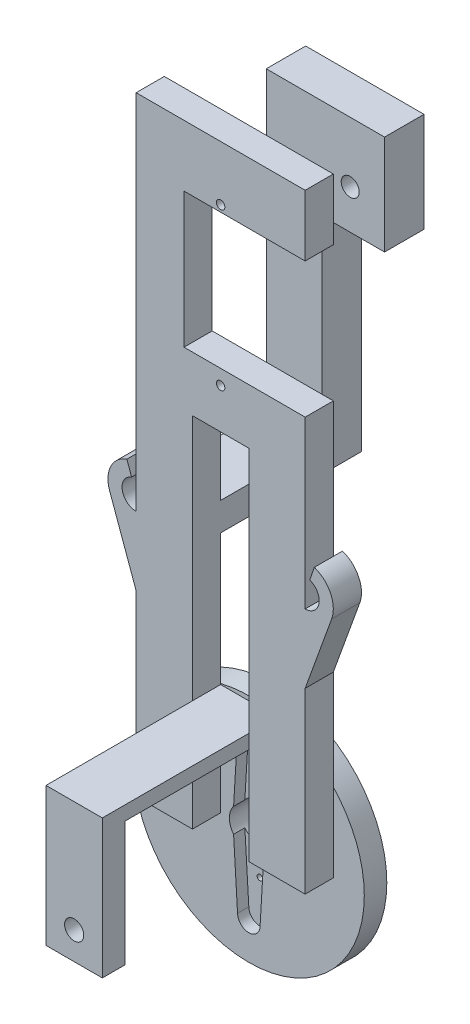
SolidWorks part; units mm, degrees
ref_plane "Front Plane" through (0, 0, 0) normal (0, 0, 1) x (1, 0, 0)
ref_plane "Top Plane" through (0, 0, 0) normal (0, 1, 0) x (1, 0, 0)
ref_plane "Right Plane" through (0, 0, 0) normal (1, 0, 0) x (0, 0, -1)
sketch "Sketch2" plane through (0, 0, 0) normal (0, 0, 1) x (1, 0, 0)
  line L0 (-32, -13.925) -> (-32.7, -2.1477)
  line L1 (-32.7, 2.1477) -> (-32, 13.925)
  line L2 (-28, 13.925) -> (-27.3, 2.1477)
  line L3 (-28, -13.925) -> (-27.3, -2.1477)
  line L4 (-28.2556, -14.0649) -> (-27.3, -2.1477) construction
  arc A1 (-28, 13.925) -> (-32, 13.925) centre (-30, 13.925) ccw
  arc A2 (-32, -13.925) -> (-28, -13.925) centre (-30, -13.925) ccw
  arc A4 (-27.3, -2.1477) -> (-27.3, 2.1477) centre (-30, 0) ccw
  arc A5 (-32.7, 2.1477) -> (-32.7, -2.1477) centre (-30, 0) ccw
  circle A6 centre (-30, 0) radius 20.5
  dimension "D1" = 41
  dimension "D2" = 2
  dimension "D3" = 2
extrude "Boss-Extrude1" add sketch "Sketch2" against normal blind 4
sketch "Sketch3" plane through (0, 0, -4) normal (0, 0, -1) x (-1, 0, 0)
  line L0 (32, 13.925) -> (32.7, 2.1477)
  line L1 (32.7, -2.1477) -> (32, -13.925)
  line L2 (28, -13.925) -> (27.3, -2.1477)
  line L3 (28, 13.925) -> (27.3, 2.1477)
  arc A0 (32.7, 2.1477) -> (27.3, 2.1477) centre (30, 0) ccw
  arc A1 (28, -13.925) -> (32, -13.925) centre (30, -13.925) ccw
  arc A2 (32, 13.925) -> (28, 13.925) centre (30, 13.925) ccw
  arc A3 (27.3, -2.1477) -> (32.7, -2.1477) centre (30, 0) ccw
extrude "Boss-Extrude2" add sketch "Sketch3" against normal blind 2
sketch "Sketch4" plane through (0, 0, 0) normal (0, 0, 1) x (1, 0, 0)
  line L0 (-50.5, 0) -> (-9.5, 0) construction
  line L1 (-30, 20.5) -> (-30, -20.5) construction
  line L3 (-45, 0) -> (-35, 0)
  line L4 (-45, 0) -> (-45, 66.4807)
  line L6 (-35, 0) -> (-35, 63.5566)
  line L8 (-45, 45) -> (-35, 45) construction
  line L9 (-25, 0) -> (-25, 63.5566)
  line L10 (-15, 0) -> (-25, 0)
  line L11 (-15, 0) -> (-15, 66.4807)
  line L13 (-45, 108.2058) -> (-15, 108.2058)
  line L14 (-45, 108.2058) -> (-45, 66.4807)
  line L15 (-35, 63.5566) -> (-25, 63.5566)
  line L16 (-15, 108.2058) -> (-15, 66.4807)
  line L17 (-30, 60.6324) -> (-30, 108.2058) construction
  line L22 (-30, 73.2926) -> (-30, 96.1526) construction
  line L24 (-33.6892, 97.3307) -> (-50033.6892, 97.3307) construction
  line L26 (-35.3887, 73.3307) -> (-50035.3887, 73.3307) construction
  line L28 (-36.5, 74.4318) -> (-36.5, 50074.4318) construction
  line L30 (-23.5, 99.0932) -> (-23.5, -49900.9068) construction
  line L33 (-36.5, 97.3307) -> (-23.5, 97.3307)
  line L34 (-36.5, 97.3307) -> (-36.5, 73.3307)
  line L35 (-36.5, 73.3307) -> (-23.5, 73.3307)
  line L36 (-23.5, 97.3307) -> (-23.5, 73.3307)
  line L37 (-30, 73.3307) -> (-30, 97.3307) construction
  line L38 (-36.5, 85.3307) -> (-23.5, 85.3307) construction
  circle A0 centre (-30, 0) radius 20.5 construction
  circle A4 centre (-30, 70.6807) radius 0.75
  circle A5 centre (-30, 98.4807) radius 0.75
  point P317 (-30, 84.7226)
  point P606 (-30, 85.3307)
  point P879 (-30, 87.3433)
  point P1483 (-40, 45)
  dimension "D4" = 1.5
  dimension "D5" = 24
  dimension "D3" = 1.5
  dimension "D6" = 13
  dimension "D1" = 5
  dimension "D2" = 10
extrude "Boss-Extrude3" add sketch "Sketch4" along normal blind 5
sketch "Sketch5" plane through (0, 0, 0) normal (0, 0, -1) x (-1, 0, 0)
  line L0 (35, 19.8809) -> (35, 63.5566) construction
  line L1 (35, 48.0311) -> (45, 48.0311)
  line L2 (35, 48.0311) -> (35, 43.0311)
  line L3 (35, 43.0311) -> (45, 43.0311)
  line L4 (45, 48.0311) -> (45, 43.0311)
  line L5 (40, 43.0311) -> (40, 48.0311) construction
  line L6 (35, 45.5311) -> (45, 45.5311) construction
  line L7 (45, 108.2058) -> (45, 13.9732) construction
  point P208 (40, 45.5311)
  dimension "D1" = 5
extrude "Boss-Extrude4" add sketch "Sketch5" along normal blind 25
sketch "Sketch6" plane through (0, 48.0311, 0) normal (0, 1, 0) x (1, 0, 0)
  line L0 (-45, 25) -> (-35, 25) construction
  line L1 (-44.9019, 25) -> (-23.9019, 25)
  line L2 (-44.9019, 25) -> (-44.9019, 18)
  line L3 (-44.9019, 18) -> (-23.9019, 18)
  line L4 (-23.9019, 25) -> (-23.9019, 18)
  line L5 (-34.4019, 18) -> (-34.4019, 25) construction
  line L6 (-44.9019, 21.5) -> (-23.9019, 21.5) construction
  point P912 (-34.4019, 21.5)
  dimension "D1" = 21
  dimension "D2" = 7
extrude "Boss-Extrude5" add sketch "Sketch6" along normal blind 52.4
sketch "Sketch7" plane through (0, 0, -25) normal (0, 0, -1) x (-1, 0, 0)
  circle A0 centre (30, 89.7307) radius 1.6
  dimension "D1" = 3.2
extrude "Cut-Extrude1" cut sketch "Sketch7" against normal blind 52.4
sketch "Sketch8" plane through (0, 0, 0) normal (0, 0, 1) x (1, 0, 0)
  line L0 (-30, 15.925) -> (-30, -15.925) construction
  arc A0 (-28, 13.925) -> (-32, 13.925) centre (-30, 13.925) ccw construction
  arc A1 (-32, -13.925) -> (-28, -13.925) centre (-30, -13.925) ccw construction
  circle A2 centre (-29.9753, 10.435) radius 0.5
  circle A3 centre (-30.02, -8.465) radius 0.5
extrude "Cut-Extrude2" cut sketch "Sketch8" against normal blind 10
sketch "Sketch9" plane through (0, 0, 5) normal (0, 0, 1) x (1, 0, 0)
  line L0 (-15, 0) -> (-15, 108.2058) construction
  line L1 (-23.5, 73.3307) -> (-15, 73.3307)
  line L2 (-23.5, 73.3307) -> (-23.5, 97.3307)
  line L3 (-23.5, 97.3307) -> (-15, 97.3307)
  line L4 (-15, 73.3307) -> (-15, 97.3307)
  line L5 (-19.25, 97.3307) -> (-19.25, 73.3307) construction
  line L6 (-23.5, 85.3307) -> (-15, 85.3307) construction
  point P568 (-19.25, 85.3307)
extrude "Cut-Extrude3" cut sketch "Sketch9" against normal blind 10
sketch "Sketch10" plane through (0, 0, 0) normal (0, 0, 1) x (1, 0, 0)
  line L0 (-30, 20.5) -> (-30, -20.5) construction
  line L1 (-25, 63.5566) -> (-25, 0) construction
  line L2 (-35, 19.7172) -> (-25, 19.7172)
  line L3 (-35, 19.7172) -> (-35, 17.2116)
  line L4 (-35, 17.2116) -> (-25, 17.2116)
  line L5 (-25, 19.7172) -> (-25, 17.2116)
  line L6 (-35, 19.7172) -> (-25, 17.2116) construction
  line L7 (-35, 17.2116) -> (-25, 19.7172) construction
  arc A0 (-25, 19.8809) -> (-35, 19.8809) centre (-30, 0) ccw construction
  arc A1 (-45, 13.9732) -> (-15, 13.9732) centre (-30, 0) ccw construction
  point P8 (-30, 18.4644)
extrude "Boss-Extrude6" add sketch "Sketch10" along normal blind 31
sketch "Sketch11" plane through (0, 0, 31) normal (0, 0, 1) x (1, 0, 0)
  line L1 (-35, 19.7172) -> (-25, 19.7172)
  line L2 (-35, 19.7172) -> (-35, -4.8872)
  line L3 (-35, -4.8872) -> (-25, -4.8872)
  line L4 (-25, 19.7172) -> (-25, -4.8872)
  line L5 (-30, -4.8872) -> (-30, 19.7172) construction
  line L6 (-35, 7.415) -> (-25, 7.415) construction
  circle A0 centre (-30, 0) radius 1.7
  point P1711 (-30, 7.415)
  dimension "D1" = 3.4
extrude "Boss-Extrude7" add sketch "Sketch11" against normal blind 4
sketch "Sketch12" plane through (0, 0, 5) normal (0, 0, 1) x (1, 0, 0)
  line L5 (-30, 63.5566) -> (-30, 8.7606) construction
  line L6 (-35, 63.5566) -> (-25, 63.5566) construction
  line L10 (-15, 0) -> (-15, 73.3307) construction
  line L11 (-14.1813, 48.702) -> (-13.3626, 51.0641)
  line L12 (-10.298, 44.6396) -> (-15, 31.6362)
  line L13 (-15, 43.8398) -> (-15, 31.6362)
  line L14 (-49.702, 44.6396) -> (-45, 31.6362)
  line L15 (-45, 43.8398) -> (-45, 31.6362)
  line L16 (-45.8187, 48.702) -> (-46.6374, 51.0641)
  arc A4 (-15, 43.8398) -> (-14.1813, 48.702) centre (-15, 46.3398) ccw
  arc A5 (-10.298, 44.6396) -> (-13.3626, 51.0641) centre (-15, 46.3398) ccw
  arc A6 (-45, 43.8398) -> (-45.8187, 48.702) centre (-45, 46.3398) cw
  arc A7 (-49.702, 44.6396) -> (-46.6374, 51.0641) centre (-45, 46.3398) cw
  dimension "D1" = 10
  dimension "D2" = 5
extrude "Boss-Extrude8" add sketch "Sketch12" against normal blind 5
sketch "Sketch13" plane through (0, 0, -25) normal (0, 0, -1) x (-1, 0, 0)
  line L0 (23.9019, 100.4311) -> (23.9019, 48.0311) construction
  line L1 (35, 48.0311) -> (23.9019, 48.0311)
  line L2 (35, 48.0311) -> (35, 82.7534)
  line L3 (35, 82.7534) -> (23.9019, 82.7534)
  line L4 (23.9019, 48.0311) -> (23.9019, 82.7534)
  line L5 (29.4509, 82.7534) -> (29.4509, 48.0311) construction
  line L6 (35, 65.3923) -> (23.9019, 65.3923) construction
  point P532 (29.4509, 65.3923)
extrude "Cut-Extrude4" cut sketch "Sketch13" against normal blind 10
